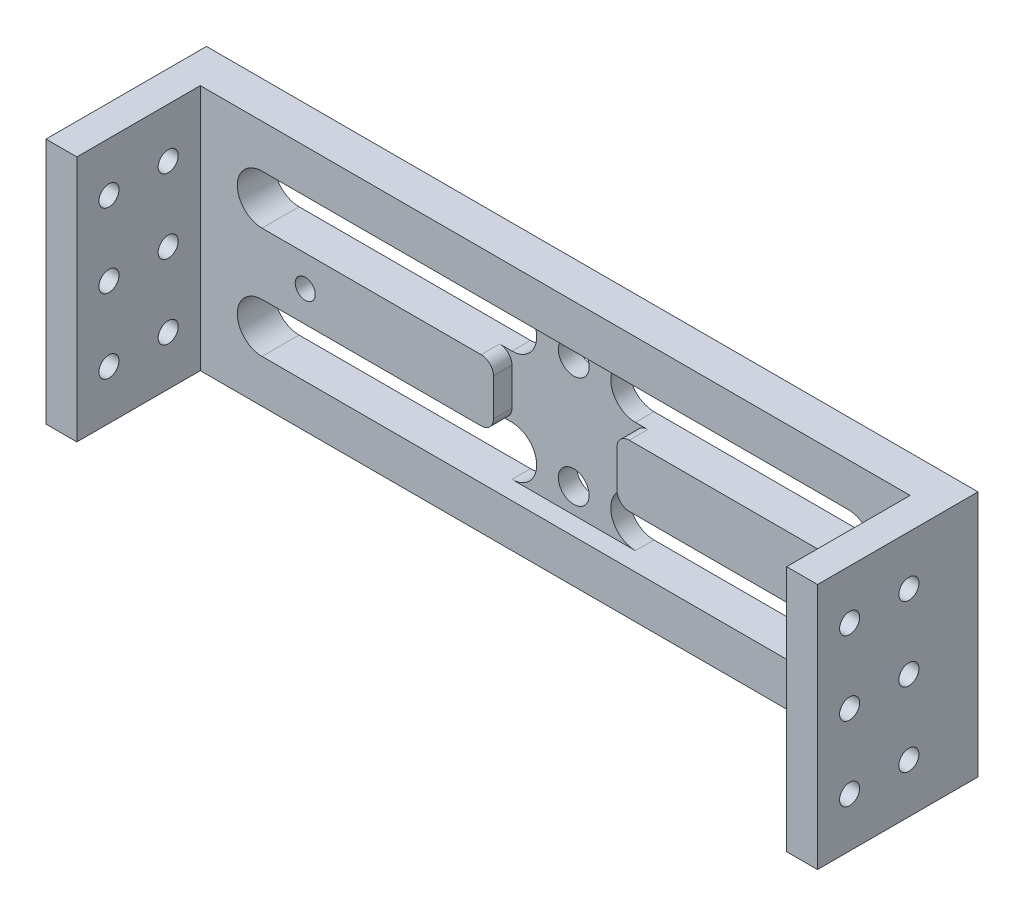
SolidWorks part; units mm, degrees
ref_plane "Plano frontal" through (0, 0, 0) normal (0, 0, 1) x (1, 0, 0)
ref_plane "Plano superior" through (0, 0, 0) normal (0, 1, 0) x (1, 0, 0)
ref_plane "Plano direito" through (0, 0, 0) normal (1, 0, 0) x (0, 0, -1)
sketch "Esboço1" plane through (0, 0, 0) normal (0, 0, 1) x (1, 0, 0)
  line L1 (32.5, -20) -> (-32.5, -20)
  line L2 (32.5, -20) -> (32.5, 20)
  line L3 (32.5, 20) -> (-32.5, 20)
  line L4 (-32.5, -20) -> (-32.5, 20)
  line L5 (32.5, -20) -> (-32.5, 20) construction
  line L6 (32.5, 20) -> (-32.5, -20) construction
  point P0 (0, 0)
  dimension "D1" = 65
  dimension "D2" = 40
extrude "Ressalto-extrusão1" add sketch "Esboço1" along normal blind 6
sketch "Esboço2" plane through (-32.5, 0, 0) normal (-1, 0, 0) x (0, 0, 1)
  line L0 (0, 20) -> (-30, 20)
  line L1 (-30, 20) -> (-30, -20)
  line L2 (-30, -20) -> (0, -20)
  line L4 (0, 20) -> (0, -20)
  line L5 (0, -20) -> (6, -20)
  line L6 (6, -20) -> (6, 20)
  line L7 (6, 20) -> (0, 20)
  line L8 (0, 20) -> (0, -20) construction
  line L9 (0, -20) -> (6, -20)
  line L10 (6, -20) -> (6, 20)
  line L11 (6, 20) -> (0, 20)
  dimension "D2" = 30
  dimension "D1" = 0
extrude "Ressalto-extrusão2" add sketch "Esboço2" along normal blind 4
sketch "Esboço3" plane through (-36.5, 0, 0) normal (-1, 0, 0) x (0, 0, 1)
  line L0 (0, 20) -> (0, -20) construction
  line L1 (0, 20) -> (0, -20) construction
  line L2 (-15, 3.125) -> (-30, 3.125)
  line L3 (0, 20) -> (-30, 20) construction
  line L4 (0, 20) -> (0, -20) construction
  line L5 (0, -20) -> (-30, -20) construction
  line L6 (-30, 20) -> (-30, -20) construction
  line L7 (-15, -20) -> (-15, 20) construction
  line L8 (0, 0) -> (-30, 0) construction
  line L9 (-30, 3.125) -> (-30, -3.125)
  line L10 (-30, -3.125) -> (-15, -3.125)
  arc A0 (-15, -3.125) -> (-15, 3.125) centre (-15, 0) ccw
  point P276 (-15, 0)
  dimension "D1" = 6.25
extrude "Corte-extrusão1" cut sketch "Esboço3" against normal through all
sketch "Esboço5" plane through (0, 0, 6) normal (0, 0, 1) x (1, 0, 0)
  line L0 (-36.5, -20) -> (32.5, -20) construction
  line L1 (-36.5, 20) -> (-30, 20)
  line L2 (-36.5, 20) -> (-36.5, -20)
  line L3 (-36.5, -20) -> (-30, -20)
  line L4 (-30, 20) -> (-30, -20)
  line L6 (-30, 20) -> (-25, 20)
  line L7 (-30, 20) -> (-30, -20)
  line L8 (-30, -20) -> (-25, -20)
  line L9 (-25, 20) -> (-25, -20)
  line L10 (-25, 20) -> (-21.5, 20)
  line L11 (-25, 20) -> (-25, -20)
  line L12 (-25, -20) -> (-21.5, -20)
  line L13 (-21.5, 20) -> (-21.5, -20)
  line M5 (32.5, 20) -> (-36.5, 20)
  line M7 (-36.5, -20) -> (32.5, -20)
  dimension "D1" = 15
  dimension "D2" = 6.5
  dimension "D3" = 5
extrude "Ressalto-extrusão4" add sketch "Esboço5" along normal blind 20 contours L9 L4 M5 M7
sketch "Esboço7" plane through (-32.5, 0, 0) normal (1, 0, 0) x (0, 0, -1)
  line L0 (15, -6.625) -> (30, -6.625)
  line L1 (30, -3.125) -> (30, -20) construction
  line L2 (30, -6.625) -> (30, 6.625)
  line L3 (30, 20) -> (30, 3.125) construction
  line L4 (30, 6.625) -> (15, 6.625)
  arc A0 (15, 6.625) -> (15, -6.625) centre (15, 0) ccw
  dimension "D1" = 13.25
extrude "Corte-extrusão3" cut sketch "Esboço7" against normal blind 1.2
sketch "Esboço8" plane through (-32.5, 0, 0) normal (1, 0, 0) x (0, 0, -1)
  line L4 (15, -6.625) -> (30, -6.625) construction
  line L5 (25.7471, -6.625) -> (28.0384, -6.625)
  line L6 (30, 6.625) -> (15, 6.625) construction
  line L7 (28.0384, 6.625) -> (25.7471, 6.625)
  arc A0 (25.7471, 6.625) -> (25.7471, -6.625) centre (15, 0) ccw
  arc A1 (28.0384, 6.625) -> (28.0384, -6.625) centre (15, 0) ccw
  dimension "D1" = 25.25
  dimension "D2" = 2
extrude "Ressalto-extrusão5" add sketch "Esboço8" along normal blind 4
sketch "Esboço11" plane through (0, 0, 6) normal (0, 0, 1) x (1, 0, 0)
  line L0 (-15, 9) -> (22.5, 9) construction
  line L1 (-15, 13) -> (22.5, 13)
  line L2 (-15, 5) -> (22.5, 5)
  line L3 (-15, -9) -> (22.5, -9) construction
  line L4 (-15, -5) -> (22.5, -5)
  line L5 (-15, -13) -> (22.5, -13)
  line L6 (32.5, -20) -> (32.5, 20) construction
  line L7 (-25, 20) -> (-25, -20) construction
  line L8 (32.5, 20) -> (-25, 20) construction
  line L9 (-25, -20) -> (32.5, -20) construction
  line L10 (3.75, 20) -> (3.75, -20) construction
  arc A0 (-15, 13) -> (-15, 5) centre (-15, 9) ccw
  arc A1 (22.5, 5) -> (22.5, 13) centre (22.5, 9) ccw
  arc A2 (-15, -5) -> (-15, -13) centre (-15, -9) ccw
  arc A3 (22.5, -13) -> (22.5, -5) centre (22.5, -9) ccw
  point P2 (3.75, 9)
  point P7 (3.75, -9)
  dimension "D1" = 10
  dimension "D2" = 10
  dimension "D3" = 7
  dimension "D4" = 7
  dimension "D5" = 10
extrude "Corte-extrusão4" cut sketch "Esboço11" against normal through all
sketch "Esboço12" plane through (-32.5, 0, 0) normal (1, 0, 0) x (0, 0, -1)
  line L14 (0, -20) -> (6, -20)
  line L15 (0, -20) -> (0, -15)
  line L16 (0, -15) -> (6, -15)
  line L17 (6, -20) -> (6, -15)
  line L18 (30, -20) -> (24, -20)
  line L19 (30, -20) -> (30, -15)
  line L20 (30, -15) -> (24, -15)
  line L21 (24, -20) -> (24, -15)
  dimension "D1" = 5
  dimension "D3" = 6
extrude "Ressalto-extrusão6" add sketch "Esboço12" along normal up to surface (65 mm away) up to face at (32.5, 0, 3)
sketch "Esboço13" plane through (0, 0, -24) normal (0, 0, 1) x (1, 0, 0)
  line L0 (32.5, -15) -> (-32.5, -15) construction
  line L1 (32.5, -20) -> (29.5, -20)
  line L2 (32.5, -20) -> (32.5, -15)
  line L3 (32.5, -15) -> (29.5, -15)
  line L4 (29.5, -20) -> (29.5, -15)
  dimension "D1" = 3
extrude "Ressalto-extrusão7" add sketch "Esboço13" along normal up to surface (18 mm away) up to face at (0, -17.5, -6)
ref_plane "Plano1" through (0, 0, 0) normal (0, 1, 0) x (1, 0, 0)
mirror "Espelhar2" about plane through (0, 0, 0) normal (0, 1, 0) of "Ressalto-extrusão6", "Ressalto-extrusão7"
sketch "Esboço15" plane through (-30, 0, 0) normal (-1, 0, 0) x (0, 0, 1)
  line L0 (6, 0) -> (26, 0) construction
  line L1 (6, 20) -> (6, -20) construction
  line L2 (26, 20) -> (26, -20) construction
  line L3 (20.8, 20) -> (20.8, -20) construction
  line L4 (26, -20) -> (6, -20) construction
  line L5 (26, 20) -> (6, 20) construction
  line L6 (11.2, 20) -> (11.2, -20) construction
  line L7 (20.8, -12) -> (11.2, -12) construction
  line L8 (20.8, 12) -> (11.2, 12) construction
  circle A0 centre (20.8, 12) radius 1.625
  circle A1 centre (11.2, 12) radius 1.625
  circle A2 centre (20.8, 0) radius 1.625
  circle A3 centre (11.2, 0) radius 1.625
  circle A4 centre (20.8, -12) radius 1.625
  circle A5 centre (11.2, -12) radius 1.625
  dimension "D5" = 3.25
  dimension "D1" = 5.2
  dimension "D2" = 5.2
  dimension "D3" = 8
  dimension "D4" = 8
extrude "Corte-extrusão5" cut sketch "Esboço15" against normal up to surface (5 mm away) up to face at (-25, 0, 16)
ref_plane "Plano2" through (32.5, 0, 0) normal (1, 0, 0) x (0, 0, -1)
sketch "Esboço18" plane through (0, 0, 6) normal (0, 0, 1) x (1, 0, 0)
  line L0 (32.5, -20) -> (32.5, 20) construction
  line L1 (32.5, -20) -> (32.5, 20)
  line L2 (32.5, 0) -> (-25, 0) construction
  line L3 (-25, 20) -> (-25, -20) construction
  line L4 (-25, 20) -> (-25, -20)
  circle A0 centre (-8, 0) radius 1.625
  dimension "D2" = 3.25
  dimension "D1" = 40.5
extrude "Corte-extrusão6" cut sketch "Esboço18" against normal up to surface (6 mm away) contours A0 L2 | L2 A0 up to face at (3.75, -9, 0)
sketch "Esboço19" plane through (0, 0, 0) normal (0, 0, -1) x (-1, 0, 0)
  circle A0 centre (8, 0) radius 2.875
  dimension "D1" = 5.75
extrude "Corte-extrusão7" cut sketch "Esboço19" against normal blind 1.5
sketch "Esboço22" plane through (-36.5, 0, 0) normal (-1, 0, 0) x (0, 0, 1)
  line L0 (-8.9896, 6.0104) -> (-15, 0) construction
  line L1 (-15, 0) -> (-8.9896, 0) construction
  line L2 (-8.9896, 0) -> (-8.9896, 6.0104) construction
  circle A0 centre (-8.9896, 6.0104) radius 1.625
  circle A1 centre (-21.0104, 6.0104) radius 1.625
  circle A2 centre (-21.0104, -6.0104) radius 1.625
  circle A3 centre (-8.9896, -6.0104) radius 1.625
  point P15 (-15, 0)
  dimension "D3" = 3.25
  dimension "D1" = 8.5
  dimension "D2" = 45
  dimension "D4" = 4
extrude "Corte-extrusão10" cut sketch "Esboço22" against normal blind 4
mirror "Espelhar3" about plane through (32.5, 0, 0) normal (1, 0, 0) of bodies 121 115
sketch "Esboço20" plane through (0, 0, 6) normal (0, 0, 1) x (1, 0, 0)
  line L0 (42.5, -13) -> (22.5, -13)
  line L1 (22.5, -13) -> (22.5, -5)
  line L3 (42.5, -5) -> (42.5, -13)
  line L4 (42.5, 5) -> (42.5, 13)
  line L5 (42.5, 13) -> (22.5, 13)
  line L6 (22.5, 13) -> (22.5, 5)
  line L8 (42.5, 5) -> (42.5, -5)
  line L9 (22.5, -5) -> (22.5, 5)
  arc A0 (22.5, 5) -> (22.5, 13) centre (22.5, 9) ccw construction
extrude "Corte-extrusão8" cut sketch "Esboço20" against normal blind 3
sketch "Esboço21" plane through (0, 0, 3) normal (0, 0, 1) x (1, 0, 0)
  line L0 (26.5, 9) -> (38.5, 9) construction
  line L1 (26.5, -9) -> (38.5, -9) construction
  arc A0 (22.5, 5) -> (22.5, 13) centre (22.5, 9) ccw construction
  arc A1 (42.5, 13) -> (42.5, 5) centre (42.5, 9) ccw construction
  arc A2 (22.5, -13) -> (22.5, -5) centre (22.5, -9) ccw construction
  arc A3 (42.5, -5) -> (42.5, -13) centre (42.5, -9) ccw construction
  circle A4 centre (32.5, 9) radius 2.5
  circle A5 centre (32.5, -9) radius 2.5
  dimension "D1" = 5
extrude "Corte-extrusão9" cut sketch "Esboço21" against normal up to surface (3 mm away) up to face at (-10.875, 0, 0)
fillet "Filete1" radius 2 4 edges at (22.5, -5, 4.5) (22.5, 5, 4.5) (42.5, 5, 4.5) (42.5, -5, 4.5)
sketch "Esboço23" plane through (0, -15, 0) normal (0, 1, 0) x (1, 0, 0)
  line L1 (97.5, 0) -> (-32.5, 0)
  line L2 (97.5, 0) -> (97.5, 30)
  line L3 (97.5, 30) -> (-32.5, 30)
  line L4 (-32.5, 0) -> (-32.5, 30)
extrude "Corte-extrusão11" cut sketch "Esboço23" against normal through all both and the other way through all
sketch "Esboço24" plane through (0, 0, 6) normal (0, 0, 1) x (1, 0, 0)
  line L1 (95, -20) -> (101.5, -20)
  line L2 (95, -20) -> (95, 20)
  line L3 (95, 20) -> (101.5, 20)
  line L4 (101.5, -20) -> (101.5, 20)
  line L5 (-36.5, 20) -> (-30, 20)
  line L6 (-36.5, 20) -> (-36.5, -20)
  line L7 (-36.5, -20) -> (-30, -20)
  line L8 (-30, 20) -> (-30, -20)
extrude "Corte-extrusão12" cut sketch "Esboço24" against normal through all
equation "\"3d\"= 0.25mm"
equation "\"D5@Esboço15\"= 3.00mm +\"3d\""
equation "\"D3@Esboço22\"=3.00mm +\"3d\""
equation "\"D2@Esboço18\"= 3.00mm +\"3d\""
equation "\"D1@Esboço3\"= 6.0mm + \"3d\""
equation "\"D1@Esboço7\"=13.00mm + \"3d\""
equation "\"D1@Esboço8\"= 25mm + \"3d\""
equation "\"D1@Esboço19\"= 5.5mm + \"3d\""
